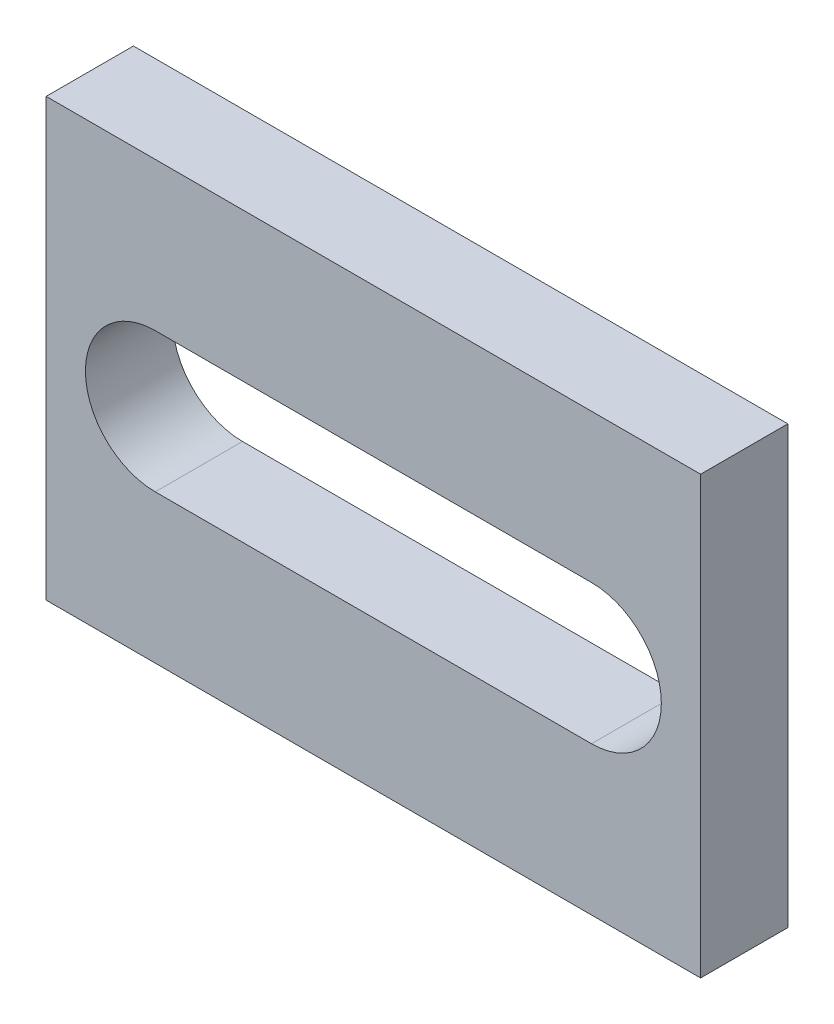
SolidWorks part; units mm, degrees
ref_plane "Front Plane" through (0, 0, 0) normal (0, 0, 1) x (1, 0, 0)
ref_plane "Top Plane" through (0, 0, 0) normal (0, 1, 0) x (1, 0, 0)
ref_plane "Right Plane" through (0, 0, 0) normal (1, 0, 0) x (0, 0, -1)
sketch "Sketch1" plane through (0, 0, 0) normal (0, 0, 1) x (1, 0, 0)
  line L0 (0, 25) -> (75, 25) construction
  line L1 (0, 0) -> (75, 0)
  line L2 (0, 0) -> (0, 50)
  line L3 (0, 50) -> (75, 50)
  line L4 (75, 0) -> (75, 50)
  line L5 (37.5, 50) -> (37.5, 0) construction
  line L7 (12.5, 33) -> (62.5, 33)
  line L8 (12.5, 17) -> (62.5, 17)
  arc A0 (12.5, 33) -> (12.5, 17) centre (12.5, 25) ccw
  arc A1 (62.5, 33) -> (62.5, 17) centre (62.5, 25) cw
  point P11 (37.5, 17)
  point P17 (37.5, 33)
  dimension "D3" = 8
  dimension "D1" = 50
  dimension "D2" = 75
  dimension "D4" = 50
extrude "Boss-Extrude1" add sketch "Sketch1" along normal blind 10
